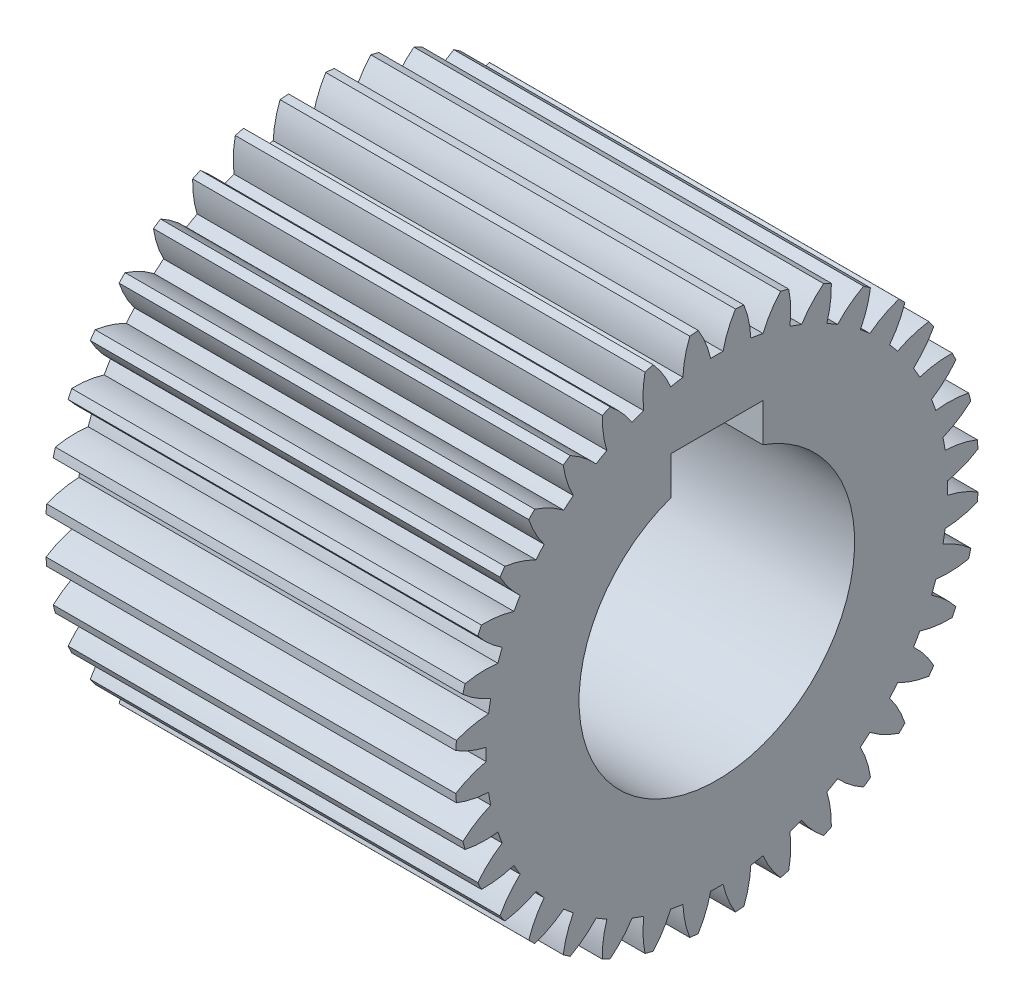
SolidWorks part; units mm, degrees
ref_plane "Plane1" through (0, 0, 0) normal (0, 0, 1) x (1, 0, 0)
ref_plane "Plane2" through (0, 0, 0) normal (0, 1, 0) x (1, 0, 0)
ref_plane "Plane3" through (0, 0, 0) normal (1, 0, 0) x (0, 0, -1)
sketch "HoldingSke" plane through (0, 0, 0) normal (0, 1, 0) x (1, 0, 0)
  line L0 (0, 0) -> (0.5393, -0.3919)
  line L1 (-15, 0) -> (100, 0) construction
  line L2 (0, 0) -> (-2.1039, 2.3779)
  line L3 (0, 0) -> (-11.863, 4.5341)
  line L4 (0, 0) -> (6.9867, 5.0761)
  line L5 (0, 0) -> (-46.8476, -17.4728)
  line L6 (0, 0) -> (-36.9717, -24.9449)
  line L7 (-2.1039, 2.3779) -> (8.6586, 51.2059)
  line L8 (-76.2, 54.61) -> (-72.9, 54.61)
  line L9 (-71.009, 38.7566) -> (-53.1078, 45.2721)
  line L10 (-76.2, 71.12) -> (104.1128, 71.12)
  line L11 (0, 0) -> (-44.6, 0)
  line L12 (-76.2, 101.6) -> (-76.147, 101.6)
  line L13 (24.9733, 27.94) -> (52.9518, 28.4284)
  line L14 (24.9733, 27.94) -> (24.9743, 27.94)
  line L15 (24.9733, 27.94) -> (100.4006, 29.5858)
  line L16 (-63.627, -1.5) -> (-12.827, -1.5)
  circle A0 centre (0, 0) radius 15
  circle A1 centre (0, 0) radius 25.124
  circle A2 centre (0, 0) radius 37.5
  circle A3 centre (0, 0) radius 15
  dimension "MHD" = 50.248
  dimension "Hub_dia" = 75
  dimension "Bore" = 30
  dimension "MBD" = 30
  dimension "Num_teeth" = 36
  dimension "Pitch" = 0.6667
  dimension "Overall_len" = 50
  dimension "Show_teeth" = 36
  dimension "Thickness" = 44.6
  dimension "OAL" = 50.0001
  dimension "T_dim" = 3.3
  dimension "Ap" = 20
  dimension "H" = 19.05
  dimension "Pitch_radius" = 180.3128
  dimension "Width" = 44.6
  dimension "Backlash" = 0.053
  dimension "Addendum_fac" = 1
  dimension "Dedendum_fac" = 1.25
  dimension "Clearance_fac" = 0.25
  dimension "Dedendum_add" = 0.001
  dimension "Module" = 1.5
sketch "BasProSke" plane through (0, 0, 0) normal (0, 1, 0) x (1, 0, 0)
  line L0 (-10, 0) -> (60, 0) construction
  line L1 (0, 0) -> (0, 28.5)
  line L2 (0, 0) -> (44.6, 0)
  line L3 (44.6, 0) -> (44.6, 28.5)
  line L4 (44.6, 28.5) -> (0, 28.5)
  dimension "Thickness" = 44.6
  dimension "Diameter" = 57
revolve "Base-Revolve" add sketch "BasProSke" angle 360 about L0
sketch "TooCutSke" plane through (0, 0, 0) normal (1, 0, 0) x (0, 0, -1)
  line L1 (0, 0) -> (0, 107) construction
  line L2 (0, 0) -> (-1.2705, 26.9701) construction
  line L3 (0, 0) -> (-4.7026, 53.7511) construction
  line L4 (-1.2705, 26.9701) -> (-2.3513, 26.8755) construction
  arc A0 (0.6756, 25.1149) -> (-0.6756, 25.1149) centre (0, 0) ccw
  arc A1 (2.0384, 28.4525) -> (-2.0384, 28.4525) centre (0, 0) ccw
  circle A2 centre (0, 0) radius 27 construction
  circle A3 centre (0, 0) radius 25.3717 construction
  arc A4 (-0.6756, 25.1149) -> (-2.0384, 28.4525) centre (-11.2153, 22.7583) ccw
  arc A5 (2.0384, 28.4525) -> (0.6756, 25.1149) centre (11.2153, 22.7583) ccw
  dimension "Root_dia" = 50.248
  dimension "Overcut_dia" = 57.0508
  dimension "Pitch_dia" = 54
  dimension "Base_dia" = 50.7434
  dimension "Flank_rad" = 10.8
  dimension "Half_ang" = 5
  dimension "Half_CT" = 1.085
extrude "ToothCut" cut sketch "TooCutSke" along normal through all
fillet "Breaks" [suppressed] radius 0.03
fillet "RootFillets" [suppressed] radius 0.376
pattern_circular "TeethCuts" count 36 every 10 about axis through (-10, 0, 0) along (1, 0, 0) of "ToothCut", "RootFillets", "Breaks"
sketch "HubNeaOneSke" plane through (0, 0, 0) normal (-1, 0, 0) x (0, 0, 1)
  circle A0 centre (0, 0) radius 25.124
  dimension "Diameter" = 50.248
extrude "HubNearOne" [suppressed] add sketch "HubNeaOneSke" along normal blind 5.4001
sketch "HubNeaBotSke" plane through (0, 0, 0) normal (-1, 0, 0) x (0, 0, 1)
  circle A0 centre (0, 0) radius 25.124
  dimension "Diameter" = 50.248
extrude "HubNearBoth" [suppressed] add sketch "HubNeaBotSke" along normal blind 2.7
ref_plane "FarPln" through (44.6, 0, 0) normal (1, 0, 0) x (0, 0, -1)
sketch "HubFarSke" plane through (44.6, 0, 0) normal (1, 0, 0) x (0, 0, -1)
  circle A0 centre (0, 0) radius 25.124
  dimension "Diameter" = 50.248
extrude "HubFar" [suppressed] add sketch "HubFarSke" along normal blind 2.7
sketch "BorSke" plane through (0, 0, 0) normal (1, 0, 0) x (0, 0, -1)
  circle A0 centre (0, 0) radius 15
  dimension "Diameter" = 30
extrude "Bore" cut sketch "BorSke" along normal mid plane 100.0001
sketch "KeySke" plane through (0, 0, 0) normal (1, 0, 0) x (0, 0, -1)
  line L0 (-5, 0) -> (-5, 18.3)
  line L1 (-5, 18.3) -> (5, 18.3)
  line L2 (5, 18.3) -> (5, 0)
  line L3 (0, 0) -> (0, 34) construction
  line L4 (-5, 0) -> (5, 0)
  dimension "Offset" = 18.3
  dimension "Width" = 10
extrude "Keyway" cut sketch "KeySke" along normal mid plane 100.0001
pattern_circular "Keyway2" [suppressed] count 2 every 90 about axis through (-10, 0, 0) along (1, 0, 0)
equation "' \"Module@HoldingSke\" = 6.35"
equation "' \"Num_teeth@HoldingSke\" = 12"
equation "' \"Ap@HoldingSke\" =  20"
equation "' \"Ap@HoldingSke\" = 20"
equation "' \"Width@HoldingSke\" = 0.5 * 25.4"
equation "' \"Hub_dia@HoldingSke\"= 1 * 25.4"
equation "' \"Hub_dia@HoldingSke\" = 1 * 25.4"
equation "' \"Overall_len@HoldingSke\" = 1.0 * 25.4"
equation "' \"Bore@HoldingSke\" = 0.75 * 25.4"
equation "' \"T_dim@HoldingSke\" = 0.1 * 25.4"
equation "' \"Width@KeySke\" = 0.25 * 25.4"
equation "' \"Show_teeth@HoldingSke\" = 13"
equation "' \"Backlash@HoldingSke\" = 0.009 * 25.4"
equation "' \"Addendum_fac@HoldingSke\" = 1.0"
equation "' \"Dedendum_fac@HoldingSke\" = 1.25"
equation "' \"Dedendum_add@HoldingSke\" = 0.00005 * 25.4"
equation "' \"Clearance_fac@HoldingSke\" = 0.25"
equation "\"Pitch@HoldingSke\" = 1 / \"Module@HoldingSke\""
equation "\"Overcut_dia@TooCutSke\" = (\"Num_teeth@HoldingSke\" + 2 * \"Addendum_fac@HoldingSke\") / \"Pitch@HoldingSke\" + 0.002 * 25.4"
equation "\"Pitch_dia@TooCutSke\" = \"Num_teeth@HoldingSke\" / \"Pitch@HoldingSke\""
equation "\"Base_dia@TooCutSke\" = \"Num_teeth@HoldingSke\" / \"Pitch@HoldingSke\" * cos((\"Ap@HoldingSke\"  * 3.14159265 / 180))"
equation "\"Root_dia@TooCutSke\" = (\"Num_teeth@HoldingSke\" + 2) / \"Pitch@HoldingSke\" - 2 * (\"Addendum_fac@HoldingSke\" + \"Dedendum_fac@HoldingSke\") / \"Pitch@HoldingSke\" - \"Dedendum_add@HoldingSke\" * 2"
equation "\"Half_ang@TooCutSke\" = 180 / \"Num_teeth@HoldingSke\""
equation "\"Half_CT@TooCutSke\" = \"Num_teeth@HoldingSke\" / \"Pitch@HoldingSke\" * sin((3.14159265 / 2 / \"Num_teeth@HoldingSke\")) / 2 - 7 * \"Backlash@HoldingSke\" / 4"
equation "\"Flank_rad@TooCutSke\" = \"Num_teeth@HoldingSke\" / \"Pitch@HoldingSke\" / 5"
equation "\"Radius@RootFillets\" = \"Clearance_fac@HoldingSke\" / \"Pitch@HoldingSke\" + \"Dedendum_add@HoldingSke\""
equation "\"Break_rad@Breaks\" = 0.02 / \"Pitch@HoldingSke\""
equation "\"Thickness@HoldingSke\" = \"Width@HoldingSke\""
equation "\"OAL@HoldingSke\" = \"Thickness@HoldingSke\""
equation "\"MHD@HoldingSke\" = (\"Num_teeth@HoldingSke\" + 2) / \"Pitch@HoldingSke\" - 2 * (\"Addendum_fac@HoldingSke\" + \"Dedendum_fac@HoldingSke\")  / \"Pitch@HoldingSke\" - \"Dedendum_add@HoldingSke\" * 2"
equation "\"MBD@HoldingSke\" = (\"Num_teeth@HoldingSke\" + 2) / \"Pitch@HoldingSke\" - 2 * (\"Addendum_fac@HoldingSke\" + \"Dedendum_fac@HoldingSke\")  / \"Pitch@HoldingSke\" - \"Dedendum_add@HoldingSke\" * 2 - 0.002 * 25.4"
equation "\"MHD@HoldingSke\" = ((sgn( \"MHD@HoldingSke\" - \"Hub_dia@HoldingSke\" )-1)*( \"MHD@HoldingSke\" - \"Hub_dia@HoldingSke\" ))/-2+ \"Hub_dia@HoldingSke\""
equation "\"MBD@HoldingSke\" = ((sgn( \"MBD@HoldingSke\" - \"Bore@HoldingSke\" )-1)*( \"MBD@HoldingSke\" - \"Bore@HoldingSke\" ))/-2+ \"Bore@HoldingSke\""
equation "\"OAL@HoldingSke\" = ((sgn( \"OAL@HoldingSke\" - \"Overall_len@HoldingSke\" )+1)*( \"OAL@HoldingSke\" - \"Overall_len@HoldingSke\" ))/2 + \"Overall_len@HoldingSke\" + 0.000002 * 25.4"
equation "\"Num_teeth@TeethCuts\" = int( \"Show_teeth@HoldingSke\" ) + 1"
equation "\"Num_teeth@TeethCuts\" = ((sgn( \"Num_teeth@TeethCuts\" - \"Num_teeth@HoldingSke\" )-1)*( \"Num_teeth@TeethCuts\" - \"Num_teeth@HoldingSke\" ))/-2+ \"Num_teeth@HoldingSke\""
equation "\"Num_teeth@TeethCuts\" = ((sgn( \"Num_teeth@TeethCuts\" - 2.0)+1)*( \"Num_teeth@TeethCuts\" - 2.0))/2 +2.0"
equation "\"Angle@TeethCuts\" = 360.0 / \"Num_teeth@HoldingSke\""
equation "\"Diameter@BasProSke\" = (\"Num_teeth@HoldingSke\" + 2 * \"Addendum_fac@HoldingSke\") / \"Pitch@HoldingSke\""
equation "\"Thickness@BasProSke\"  = \"Thickness@HoldingSke\""
equation "' \"Fillet_rad@BasProSke\" =  \"Thickness@HoldingSke\" * 0.05"
equation "' \"Fillet_rad@BasProSke\" = \"Thickness@HoldingSke\" * 0.05"
equation "\"MHD@HoldingSke\" = ((sgn( \"MHD@HoldingSke\" - \"Root_dia@TooCutSke\" )-1)*( \"MHD@HoldingSke\" - \"Root_dia@TooCutSke\" ))/-2+ \"Root_dia@TooCutSke\""
equation "\"Diameter@HubNeaOneSke\" = \"MHD@HoldingSke\""
equation "\"Length@HubNearOne\" = \"OAL@HoldingSke\" - \"Thickness@BasProSke\""
equation "\"Diameter@HubNeaBotSke\" = \"MHD@HoldingSke\""
equation "\"Length@HubNearBoth\" = ( \"OAL@HoldingSke\" - \"Thickness@BasProSke\" ) / 2.0"
equation "\"Thickness@FarPln\" = \"Thickness@BasProSke\""
equation "\"Diameter@HubFarSke\" = \"MHD@HoldingSke\""
equation "\"Length@HubFar\" = ( \"OAL@HoldingSke\" - \"Thickness@BasProSke\" ) / 2.0"
equation "\"Diameter@BorSke\" = \"MBD@HoldingSke\""
equation "\"D1@Bore\" = \"OAL@HoldingSke\" * 2.0"
equation "\"D1@Keyway\" = \"OAL@HoldingSke\" * 2.0"
equation "\"Offset@KeySke\" = \"T_dim@HoldingSke\" + \"MBD@HoldingSke\" / 2.0"
